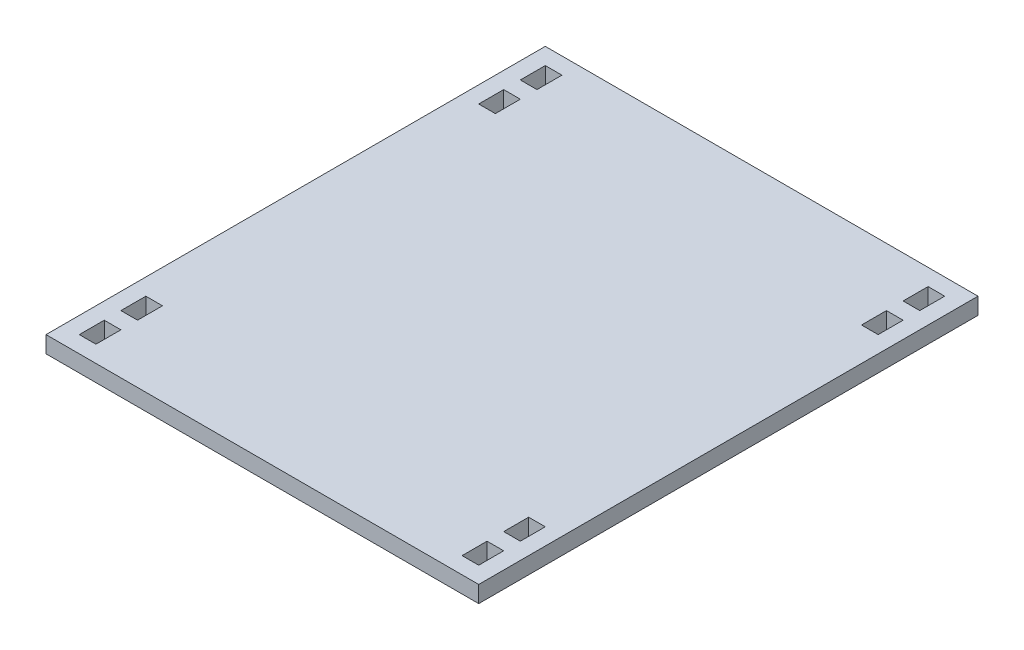
SolidWorks part; units mm, degrees
ref_plane "Front Plane" through (0, 0, 0) normal (0, 0, 1) x (1, 0, 0)
ref_plane "Top Plane" through (0, 0, 0) normal (0, 1, 0) x (1, 0, 0)
ref_plane "Right Plane" through (0, 0, 0) normal (1, 0, 0) x (0, 0, -1)
sketch "Sketch1" plane through (0, 0, 0) normal (0, 1, 0) x (1, 0, 0)
  line L1 (41.275, -47.625) -> (-41.275, -47.625)
  line L2 (41.275, -47.625) -> (41.275, 47.625)
  line L3 (41.275, 47.625) -> (-41.275, 47.625)
  line L4 (-41.275, -47.625) -> (-41.275, 47.625)
  line L5 (41.275, -47.625) -> (-41.275, 47.625) construction
  line L6 (41.275, 47.625) -> (-41.275, -47.625) construction
  point P0 (0, 0)
  dimension "D1" = 82.55
  dimension "D2" = 95.25
extrude "Boss-Extrude1" add sketch "Sketch1" along normal blind 3.175
sketch "Sketch2" plane through (0, 3.175, 0) normal (0, 1, 0) x (1, 0, 0)
  line L0 (-38.1, 39.6875) -> (-38.1, 44.45)
  line L1 (-34.925, 36.5125) -> (-38.1, 36.5125)
  line L2 (-34.925, 36.5125) -> (-34.925, 39.6875) construction
  line L3 (-34.925, 39.6875) -> (-38.1, 39.6875)
  line L4 (-38.1, 36.5125) -> (-38.1, 39.6875) construction
  line L5 (-34.925, 36.5125) -> (-38.1, 39.6875) construction
  line L6 (-34.925, 39.6875) -> (-38.1, 36.5125) construction
  line L7 (-38.1, 44.45) -> (-34.925, 44.45)
  line L8 (-34.925, 44.45) -> (-34.925, 39.6875)
  line L9 (-34.925, 36.5125) -> (-34.925, 31.75)
  line L10 (-34.925, 31.75) -> (-38.1, 31.75)
  line L11 (-38.1, 31.75) -> (-38.1, 36.5125)
  line L12 (-41.275, 47.625) -> (-41.275, -47.625) construction
  line L13 (41.275, 47.625) -> (-41.275, 47.625) construction
  point P0 (-36.5125, 38.1)
  dimension "D1" = 3.175
  dimension "D2" = 3.175
  dimension "D3" = 4.7625
  dimension "D4" = 3.175
  dimension "D5" = 3.175
extrude "Cut-Extrude1" cut sketch "Sketch2" against normal through all contours L11 L1 L9 L10 | L8 L3 L0 L7
pattern_linear "LPattern1" count 2 spacing 76.2 along (0, 0, 1) count 2 spacing 73.025 along (1, 0, 0) of "Cut-Extrude1"
